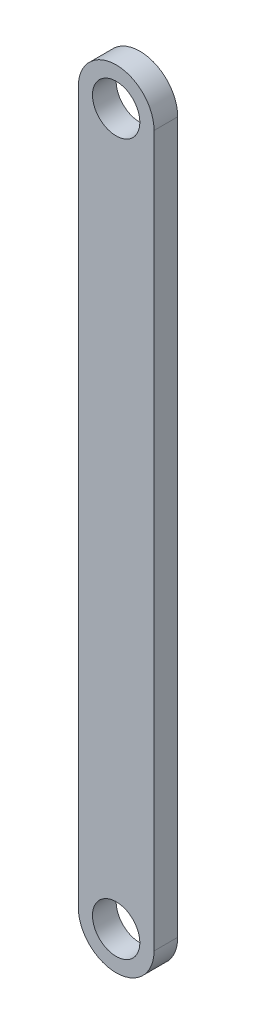
SolidWorks part; units mm, degrees
ref_plane "前基準面" through (0, 0, 0) normal (0, 0, 1) x (1, 0, 0)
ref_plane "上基準面" through (0, 0, 0) normal (0, 1, 0) x (1, 0, 0)
ref_plane "右基準面" through (0, 0, 0) normal (1, 0, 0) x (0, 0, -1)
sketch "草圖1" plane through (0, 0, 0) normal (0, 0, 1) x (1, 0, 0)
  line L0 (0, 11.3208) -> (0, -3.6792) construction
  line L1 (0.8, 11.3208) -> (0.8, -3.6792)
  line L2 (-0.8, 11.3208) -> (-0.8, -3.6792)
  arc A0 (0.8, 11.3208) -> (-0.8, 11.3208) centre (0, 11.3208) ccw
  arc A1 (-0.8, -3.6792) -> (0.8, -3.6792) centre (0, -3.6792) ccw
  circle A2 centre (0, 11.3208) radius 0.5
  circle A3 centre (0, -3.6792) radius 0.5
  point P2 (0, 3.8208)
  dimension "D2" = 1
  dimension "D3" = 0.8
  dimension "D4" = 1
  dimension "D1" = 15
extrude "填料-伸長1" add sketch "草圖1" along normal blind 0.5
